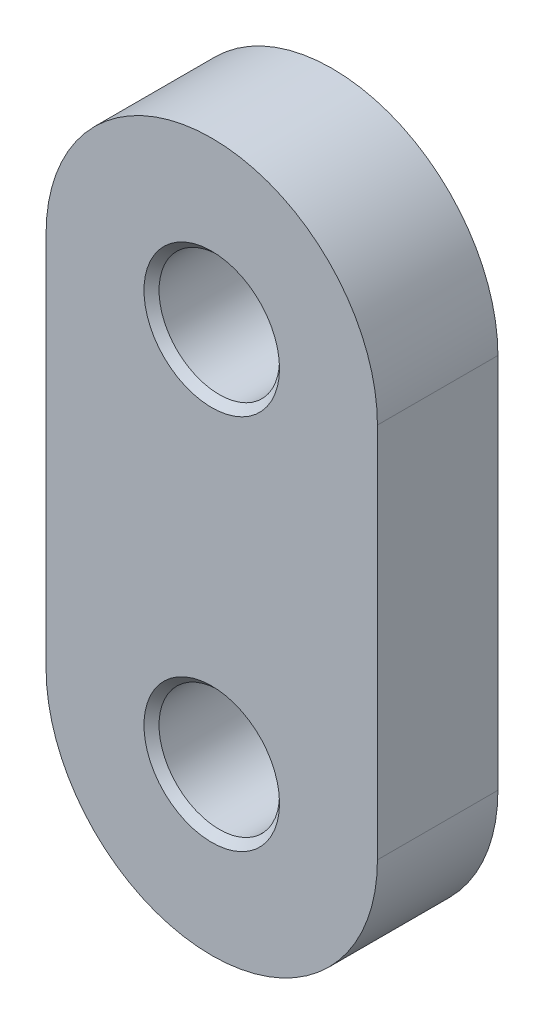
SolidWorks part; units mm, degrees
material "PW40:1:Sc:0:Re:24:"
ref_plane "Plane1" through (0, 0, 0) normal (0, 0, 1) x (1, 0, 0)
ref_plane "Plane2" through (0, 0, 0) normal (0, 1, 0) x (1, 0, 0)
ref_plane "Plane3" through (0, 0, 0) normal (1, 0, 0) x (0, 0, -1)
sketch "Esquisse1" plane through (0, 0, 0) normal (0, 0, 1) x (1, 0, 0)
  line L0 (-11, 0) -> (-11, -25)
  line L1 (11, -25) -> (11, 0)
  arc A0 (-11, -25) -> (11, -25) centre (0, -25) ccw
  arc A1 (11, 0) -> (-11, 0) centre (0, 0) ccw
  dimension "D1" = 22
  dimension "D2" = 25
extrude "Base-Extrusion" add sketch "Esquisse1" along normal blind 8
sketch "Esquisse2" plane through (0, 0, 8) normal (0, 0, 1) x (1, 0, 0)
  circle A0 centre (0, 0) radius 4
  dimension "D1" = 8
extrude "Enlèv. mat.-Extru.1" cut sketch "Esquisse2" against normal through all
sketch "Esquisse3" plane through (-1.4906, -22.4003, 8) normal (0, 0, 1) x (1, 0, 0)
  circle A0 centre (1.4906, -2.5997) radius 4
  arc A2 (-9.5094, -2.5997) -> (12.4906, -2.5997) centre (1.4906, -2.5997) ccw construction
  dimension "D1" = 8
extrude "Enlèv. mat.-Extru.2" cut sketch "Esquisse3" against normal through all
chamfer "Chanfrein1" distance 0.5 angle 45 4 edges at (4, 0, 0) (4, 0, 8) (4, -25, 0) (4, -25, 8)
